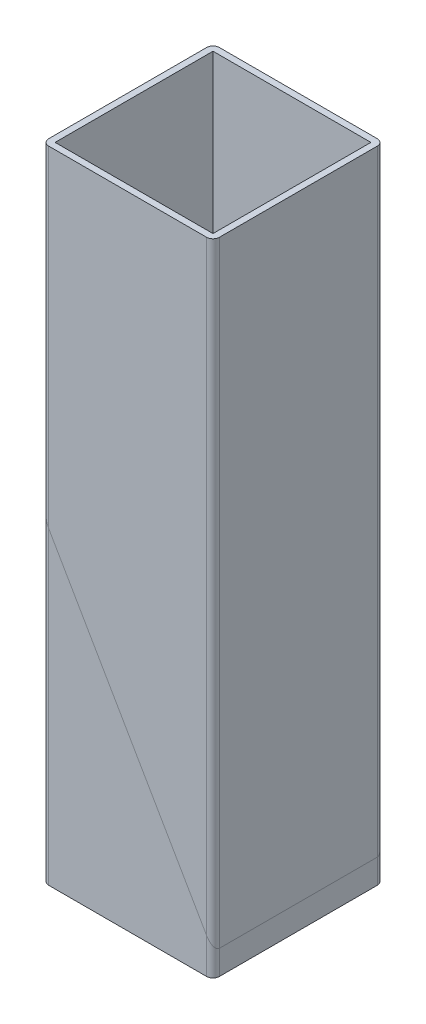
SolidWorks part; units mm, degrees
ref_plane "前视基准面" through (0, 0, 0) normal (0, 0, 1) x (1, 0, 0)
ref_plane "上视基准面" through (0, 0, 0) normal (0, 1, 0) x (1, 0, 0)
ref_plane "右视基准面" through (0, 0, 0) normal (1, 0, 0) x (0, 0, -1)
sketch "草图1" plane through (0, 0, 0) normal (0, 1, 0) x (1, 0, 0)
  line L1 (-40, 40) -> (40, 40)
  line L2 (-40, 40) -> (-40, -40)
  line L3 (-40, -40) -> (40, -40)
  line L4 (40, 40) -> (40, -40)
  line L5 (-40, 40) -> (40, -40) construction
  line L6 (-40, -40) -> (40, 40) construction
  line L7 (-37, 37) -> (37, 37)
  line L8 (-37, 37) -> (-37, -37)
  line L9 (-37, -37) -> (37, -37)
  line L10 (37, 37) -> (37, -37)
  line L11 (-37, 37) -> (37, -37) construction
  line L12 (-37, -37) -> (37, 37) construction
  point P0 (0, 0)
  point P6 (0, 0)
  dimension "D1" = 80
  dimension "D2" = 80
  dimension "D3" = 74
extrude "凸台-拉伸1" add sketch "草图1" along normal blind 300
fillet "圆角1" radius 3 4 edges at (-40, 150, 40) (-40, 150, -40) (40, 150, 40) (40, 150, -40)
sketch "草图2" plane through (0, 0, 40) normal (0, 0, 1) x (1, 0, 0)
  line L0 (-40, 0) -> (-40, 150) construction
  line L1 (-40, 0) -> (-40, 300) construction
  line L2 (-40, 150) -> (46.4149, 0.3251)
  line L3 (40, 0) -> (40, 11.4359) construction
  line L4 (40, 300) -> (40, 0) construction
  line L5 (40, 11.4359) -> (40, 61.4359) construction
  line L6 (40, 61.4359) -> (11.1325, 61.4359) construction
  point P15 (13.4736, 49.0281)
  dimension "D1" = 150
  dimension "D2" = 30
  dimension "D3" = 11.4359
  dimension "D4" = 50
  dimension "D5" = 28.8675
  dimension "D6" = 57.735
split "分割1" trim tools "草图2" bodies to split 106 resulting bodies 107 108
